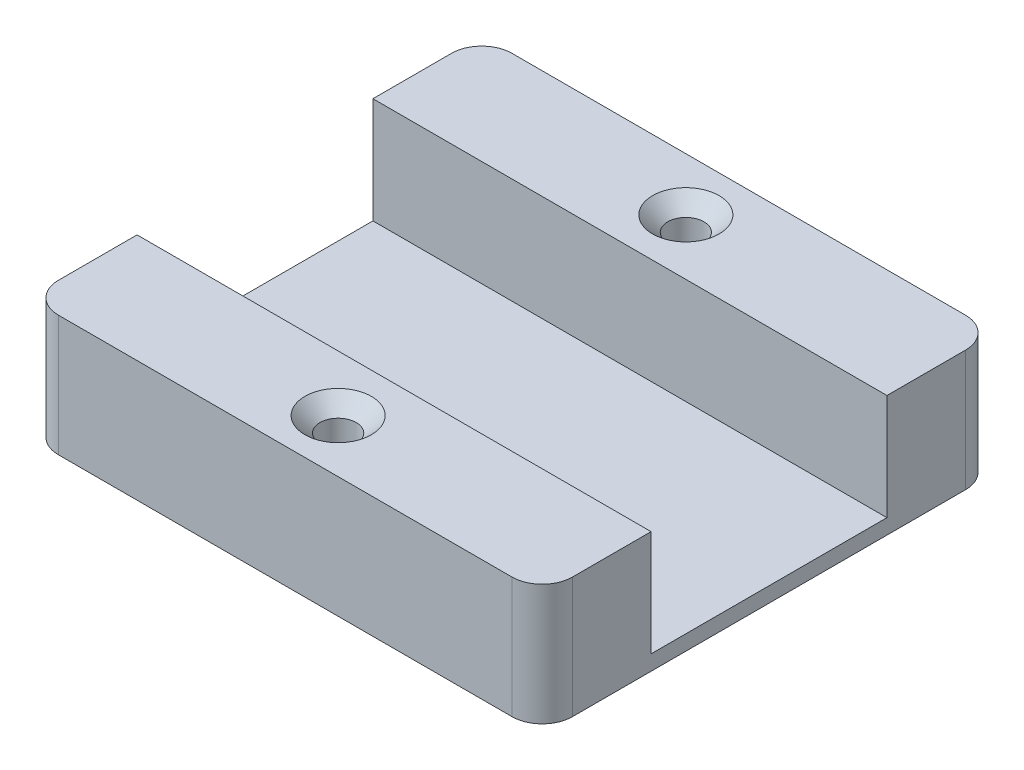
SolidWorks part; units mm, degrees
ref_plane "Front Plane" through (0, 0, 0) normal (0, 0, 1) x (1, 0, 0)
ref_plane "Top Plane" through (0, 0, 0) normal (0, 1, 0) x (1, 0, 0)
ref_plane "Right Plane" through (0, 0, 0) normal (1, 0, 0) x (0, 0, -1)
sketch "Sketch1" plane through (0, 0, 0) normal (0, 1, 0) x (1, 0, 0)
  line L0 (17, 4.7) -> (17, 15)
  line L1 (0, 0) -> (17, 0)
  line L2 (0, 0) -> (0, 15)
  line L3 (0, 15) -> (17, 15)
  line L4 (17, 0) -> (17, 2.3)
  arc A0 (17, 4.7) -> (17, 2.3) centre (17, 3.5) ccw
  dimension "D1" = 2.4
  dimension "D2" = 3.5
  dimension "D3" = 15
  dimension "D4" = 17
extrude "Boss-Extrude1" add sketch "Sketch1" along normal blind 8
sketch "Sketch2" plane through (17, 0, 0) normal (1, 0, 0) x (0, 0, -1)
  line L0 (4.7, 0) -> (15, 0) construction
  line L1 (15, 8) -> (7.2, 8)
  line L2 (15, 8) -> (15, 1)
  line L3 (15, 1) -> (7.2, 1)
  line L4 (7.2, 8) -> (7.2, 1)
  dimension "D1" = 1
  dimension "D2" = 7.8
extrude "Cut-Extrude1" cut sketch "Sketch2" against normal through all
chamfer "Chamfer1" distance 1 angle 45 1 edges at (15.8, 8, -3.5)
mirror "Mirror1" about plane through (17, 8, -4.7) normal (-1, 0, 0) of bodies 102
mirror "Mirror2" about plane through (0, 8, -15) normal (0, 0, 1) of bodies 103
fillet "Fillet1" radius 2 4 edges at (0, 4, -30) (34, 4, -30) (0, 4, 0) (34, 4, 0)
